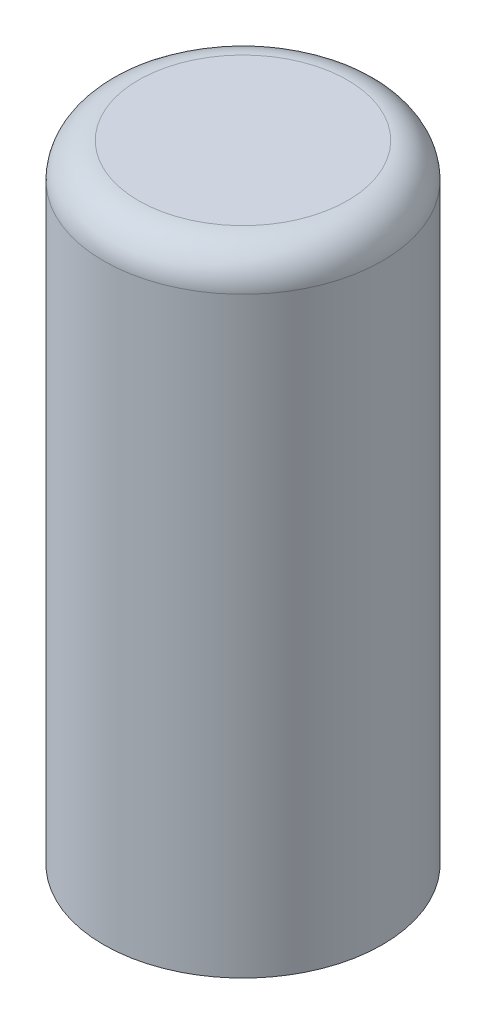
SolidWorks part; units mm, degrees
ref_plane "Front Plane" through (0, 0, 0) normal (0, 0, 1) x (1, 0, 0)
ref_plane "Top Plane" through (0, 0, 0) normal (0, 1, 0) x (1, 0, 0)
ref_plane "Right Plane" through (0, 0, 0) normal (1, 0, 0) x (0, 0, -1)
sketch "Sketch1" plane through (0, 0, 0) normal (0, 1, 0) x (1, 0, 0)
  circle A0 centre (0, 0) radius 4
  dimension "D1" = 8
extrude "Boss-Extrude1" add sketch "Sketch1" along normal blind 10
sketch "Sketch2" plane through (0, 0, 0) normal (0, -1, 0) x (1, 0, 0)
  line L0 (-3.0341, -0.5) -> (3.0341, -0.5)
  line L1 (-3.0341, 0.5) -> (3.0341, 0.5)
  line L2 (0, -0.5) -> (0, 0.5) construction
  arc A0 (-3.0341, -0.5) -> (3.0341, -0.5) centre (0, 0) ccw
  circle A1 centre (0, 0) radius 4
  circle A2 centre (0, 0) radius 4
  arc A3 (3.0341, 0.5) -> (-3.0341, 0.5) centre (0, 0) ccw
  point P10 (0, 0)
  dimension "D2" = 6.15
  dimension "D3" = 1
  dimension "D1" = 0
extrude "Boss-Extrude2" add sketch "Sketch2" along normal blind 8
fillet "Fillet3" radius 1 1 edges at (0, 10, 4)
